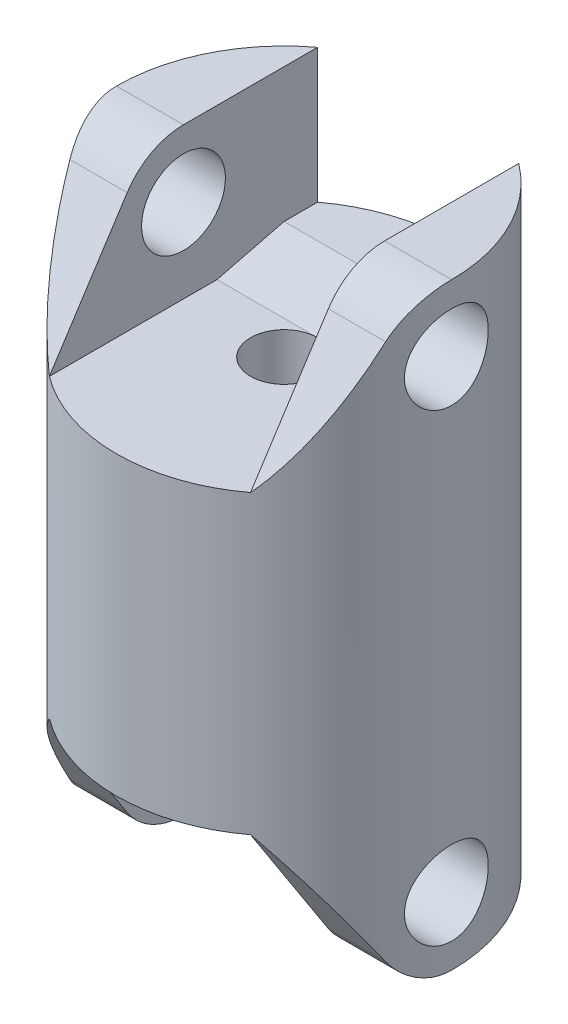
SolidWorks part; units mm, degrees
ref_plane "Front Plane" through (0, 0, 0) normal (0, 0, 1) x (1, 0, 0)
ref_plane "Top Plane" through (0, 0, 0) normal (0, 1, 0) x (1, 0, 0)
ref_plane "Right Plane" through (0, 0, 0) normal (1, 0, 0) x (0, 0, -1)
sketch "Sketch1" plane through (0, 0, 0) normal (0, 1, 0) x (1, 0, 0)
  circle A0 centre (0, 0) radius 12.7
  dimension "D1" = 25.4
extrude "Boss-Extrude1" add sketch "Sketch1" along normal blind 45.3136
sketch "Sketch2" plane through (0, 45.3136, 0) normal (0, 1, 0) x (1, 0, 0)
  line L0 (7.62, 10.16) -> (7.62, -10.16)
  line L1 (-7.62, 10.16) -> (-7.62, -10.16)
  arc A0 (-7.62, -10.16) -> (7.62, -10.16) centre (0, 0) ccw
  arc A1 (7.62, 10.16) -> (-7.62, 10.16) centre (0, 0) ccw
  dimension "D2" = 25.4
  dimension "D1" = 7.62
  dimension "D3" = 7.62
extrude "Cut-Extrude1" cut sketch "Sketch2" against normal blind 11.43
sketch "Sketch3" plane through (0, 0, 0) normal (0, -1, 0) x (1, 0, 0)
  line L4 (-7.62, 10.16) -> (-7.62, -10.16)
  line L6 (7.62, 10.16) -> (7.62, -10.16)
  arc A4 (-7.62, -10.16) -> (7.62, -10.16) centre (0, 0) ccw
  arc A5 (7.62, 10.16) -> (-7.62, 10.16) centre (0, 0) ccw
  dimension "D1" = 7.62
  dimension "D2" = 25.4
  dimension "D3" = 7.62
extrude "Cut-Extrude2" cut sketch "Sketch3" against normal blind 11.43
sketch "Sketch4" plane through (-7.62, 0, 0) normal (1, 0, 0) x (0, 0, -1)
  line L0 (10.16, 45.3136) -> (-10.16, 45.3136) construction
  line L6 (0, 45.3136) -> (-10.16, 45.3136)
  line L7 (-10.16, 45.3136) -> (-10.16, 33.8836)
  line L10 (-4.2649, 42.9935) -> (-10.16, 33.8836)
  line L16 (-10.16, 11.43) -> (-10.16, 0)
  line L17 (-10.16, 0) -> (0, 0)
  line L18 (-4.2649, 2.3201) -> (-10.16, 11.43)
  line L19 (-10.16, 0) -> (10.16, 0) construction
  circle A0 centre (0, 40.2336) radius 3.175
  circle A2 centre (0, 5.08) radius 3.175
  arc A3 (0, 45.3136) -> (-4.2649, 42.9935) centre (0, 40.2336) ccw
  arc A5 (0, 0) -> (-4.2649, 2.3201) centre (0, 5.08) cw
  dimension "D1" = 6.35
  dimension "D3" = 6.35
  dimension "D2" = 5.08
  dimension "D4" = 5.08
  dimension "D5" = 0
extrude "Cut-Extrude3" cut sketch "Sketch4" against normal through all both and the other way through all
sketch "Sketch5" plane through (0, 33.8836, 0) normal (0, 1, 0) x (1, 0, 0)
  circle A0 centre (0, 0) radius 2.54
  dimension "D1" = 5.08
extrude "Cut-Extrude4" cut sketch "Sketch5" against normal through all
sketch "Sketch6" plane through (-7.62, 0, 0) normal (1, 0, 0) x (0, 0, -1)
  line L0 (2.54, 33.8836) -> (10.16, 33.8836)
  line L1 (10.16, 33.8836) -> (-10.16, 33.8836) construction
  line L2 (10.16, 33.8836) -> (10.16, 45.3136) construction
  line L3 (10.16, 33.8836) -> (10.16, 35.1536)
  line L4 (10.16, 35.1536) -> (7.62, 35.1536)
  line L5 (7.62, 35.1536) -> (2.54, 33.8836)
  point P7 (0, 33.8836)
  dimension "D1" = 2.54
  dimension "D2" = 1.27
  dimension "D3" = 2.54
extrude "Boss-Extrude2" add sketch "Sketch6" along normal up to surface (15.24 mm away) up to face at (7.62, 40.2336, -3.175)
sketch "Sketch7" plane through (0, 33.8836, 0) normal (0, 1, 0) x (1, 0, 0)
  line L0 (-7.62, 10.16) -> (7.62, 10.16)
  arc A0 (-7.62, 10.16) -> (7.62, 10.16) centre (0, 0) cw
  arc M1 (7.62, 10.16) -> (-7.62, 10.16) centre (0, 0) ccw
  line M2 (-7.62, 10.16) -> (7.62, 10.16)
extrude "Boss-Extrude3" add sketch "Sketch7" along normal up to surface (1.27 mm away) contours M2 M1 up to face at (0, 35.1536, -8.89)
